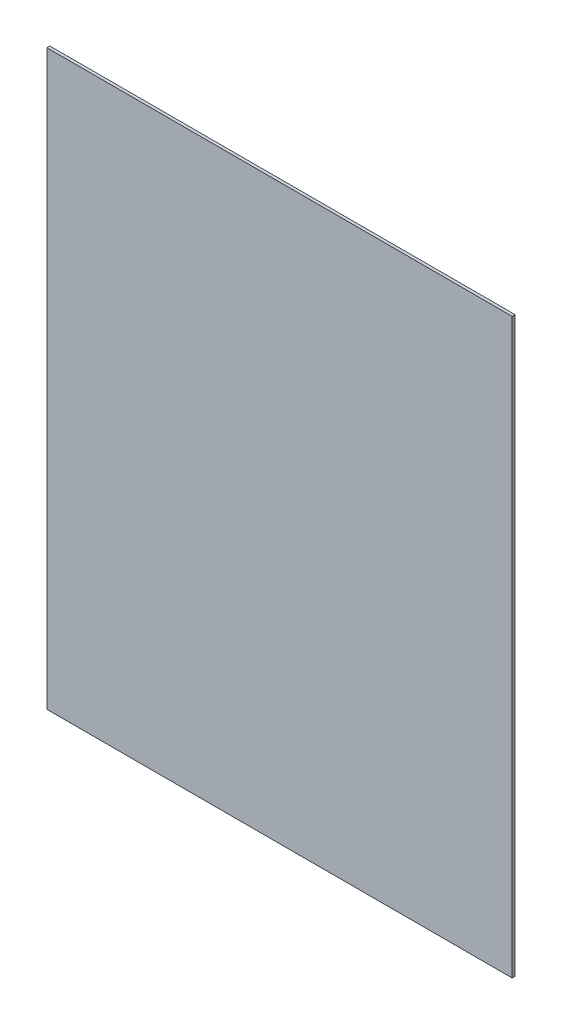
SolidWorks part; units mm, degrees
ref_plane "Front Plane" through (0, 0, 0) normal (0, 0, 1) x (1, 0, 0)
ref_plane "Top Plane" through (0, 0, 0) normal (0, 1, 0) x (1, 0, 0)
ref_plane "Right Plane" through (0, 0, 0) normal (1, 0, 0) x (0, 0, -1)
sketch "Sketch1" plane through (0, 0, 0) normal (0, 0, 1) x (1, 0, 0)
  line L1 (-14.25, 17.55) -> (14.25, 17.55)
  line L2 (-14.25, 17.55) -> (-14.25, -17.55)
  line L3 (-14.25, -17.55) -> (14.25, -17.55)
  line L4 (14.25, 17.55) -> (14.25, -17.55)
  line L5 (-14.25, 17.55) -> (14.25, -17.55) construction
  line L6 (-14.25, -17.55) -> (14.25, 17.55) construction
  point P0 (0, 0)
  dimension "D1" = 28.5
  dimension "D2" = 35.1
extrude "Boss-Extrude1" add sketch "Sketch1" along normal blind 0.18
